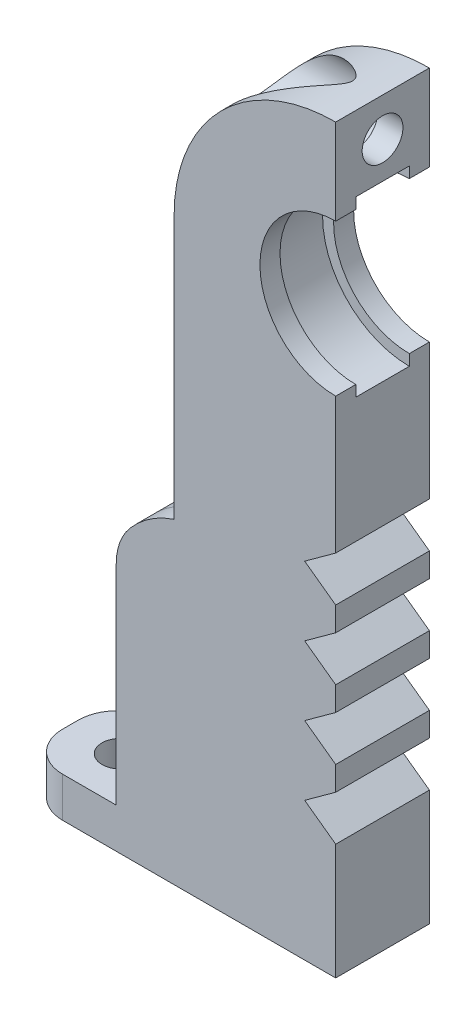
SolidWorks part; units mm, degrees
ref_plane "Front Plane" through (0, 0, 0) normal (0, 0, 1) x (1, 0, 0)
ref_plane "Top Plane" through (0, 0, 0) normal (0, 1, 0) x (1, 0, 0)
ref_plane "Right Plane" through (0, 0, 0) normal (1, 0, 0) x (0, 0, -1)
sketch "Sketch2" plane through (0, 0, 0) normal (0, 0, 1) x (1, 0, 0)
  line L0 (0, 24.5192) -> (0, -19.6154) construction
  line L1 (-22.1654, 0) -> (0, 0) construction
  line L2 (0, -11.11) -> (0, -27.11)
  line L3 (-20.69, 0) -> (-20.69, -33.7064)
  line L4 (0, -74.23) -> (-39.96, -74.23)
  line L5 (-39.96, -74.23) -> (-39.96, -69.11)
  line L6 (-28.1, -42.31) -> (-28.1, -69.11)
  line L7 (-28.1, -69.11) -> (-39.96, -69.11)
  line L9 (0, 11.11) -> (0, 20.69)
  line L10 (11.11, 0) -> (17.0654, 0) construction
  line L11 (0, -74.23) -> (7.8391, -74.23) construction
  line L12 (7.8391, -74.23) -> (7.8391, -63.37) construction
  line L13 (0, -32.87) -> (0, -35.95)
  line L14 (0, -41.71) -> (0, -44.79)
  line L15 (0, -50.55) -> (0, -53.63)
  line L16 (0, -59.39) -> (-3.97, -56.51)
  line L17 (-3.97, -56.51) -> (0, -53.63)
  line L18 (0, -59.39) -> (0, -74.23)
  line L19 (-3.97, -47.67) -> (-16.74, -47.67) construction
  line L20 (-16.74, -47.67) -> (-16.74, -45.66) construction
  line L21 (0, -50.55) -> (-3.97, -47.67)
  line L23 (-3.97, -47.67) -> (0, -44.79)
  line L28 (0, -41.71) -> (-3.97, -38.83)
  line L29 (-3.97, -38.83) -> (0, -35.95)
  line L34 (0, -32.87) -> (-3.97, -29.99)
  line L35 (-3.97, -29.99) -> (0, -27.11)
  arc A0 (0, 11.11) -> (0, -11.11) centre (0, 0) ccw
  arc A1 (0, 20.69) -> (-20.69, 0) centre (0, 0) ccw
  arc A2 (-26.3413, -37.5172) -> (-28.1, -42.31) centre (-20.69, -42.31) ccw
  arc A4 (-20.69, -33.7064) -> (-26.3413, -37.5172) centre (-16.74, -45.66) ccw
  dimension "D1" = 22.22
  dimension "D2" = 9.58
  dimension "D3" = 63.12
  dimension "D6" = 39.96
  dimension "D7" = 5.12
  dimension "D8" = 11.86
  dimension "D9" = 10.86
  dimension "D10" = 8.84
  dimension "D11" = 8.84
  dimension "D12" = 8.84
  dimension "D13" = 5.76
  dimension "D14" = 5.76
  dimension "D15" = 5.76
  dimension "D16" = 5.76
  dimension "D17" = 16
  dimension "D18" = 71.917
  dimension "D19" = 71.917
  dimension "D20" = 71.917
  dimension "D21" = 71.917
  dimension "D22" = 12.77
  dimension "D23" = 2.01
extrude "Boss-Extrude1" add sketch "Sketch2" along normal mid plane 6.86
sketch "Sketch4" plane through (0, 0, 3.43) normal (0, 0, 1) x (1, 0, 0)
  line L0 (-39.96, -69.11) -> (-39.96, -74.23)
  line L1 (-39.96, -74.23) -> (0, -74.23)
  line L2 (0, -74.23) -> (0, -59.39)
  line L3 (0, -59.39) -> (-3.97, -56.51)
  line L4 (0, -59.39) -> (-3.97, -56.51) construction
  line L5 (-3.97, -56.51) -> (0, -53.63)
  line L6 (0, -53.63) -> (0, -50.55)
  line L7 (0, -50.55) -> (-3.97, -47.67)
  line L8 (-3.97, -47.67) -> (0, -44.79)
  line L9 (0, -44.79) -> (0, -41.71)
  line L10 (0, -41.71) -> (-3.97, -38.83)
  line L11 (-3.97, -38.83) -> (0, -35.95)
  line L12 (-3.97, -38.83) -> (0, -35.95) construction
  line L13 (0, -35.95) -> (0, -32.87)
  line L14 (0, -32.87) -> (-3.97, -29.99)
  line L15 (-3.97, -29.99) -> (0, -27.11)
  line L16 (0, 20.69) -> (0, 9.7)
  line L17 (0, -27.11) -> (0, -9.7)
  line L18 (-20.69, -33.7073) -> (-20.69, 0)
  line L19 (-39.96, -69.11) -> (-28.1, -69.11)
  line L20 (-28.1, -42.31) -> (-28.1, -69.11) construction
  line L21 (-28.1, -69.11) -> (-39.96, -69.11) construction
  line L22 (-28.1, -69.11) -> (-28.1, -42.31)
  line L23 (-3.97, -47.67) -> (-16.739, -47.67) construction
  line L24 (-16.739, -47.67) -> (-16.739, -45.6641) construction
  arc A0 (0, 9.7) -> (0, -9.7) centre (0, 0) ccw
  arc A1 (0, 20.69) -> (-20.69, 0) centre (0, 0) ccw
  arc A2 (-26.3389, -37.5144) -> (-28.1, -42.31) centre (-20.69, -42.31) ccw
  arc A3 (-20.69, -33.7073) -> (-26.3389, -37.5144) centre (-16.739, -45.6641) ccw
  dimension "D1" = 10.99
  dimension "D2" = 12.769
  dimension "D3" = 2.0059
extrude "Boss-Extrude3" add sketch "Sketch4" along normal blind 2.57
sketch "Sketch5" plane through (0, 0, -3.43) normal (0, 0, -1) x (-1, 0, 0)
  line L0 (0, 20.69) -> (0, 9.7)
  line L1 (0, -9.7) -> (0, -27.11)
  line L2 (0, -27.11) -> (3.97, -29.99)
  line L3 (3.97, -29.99) -> (0, -32.87)
  line L4 (0, -32.87) -> (0, -35.95)
  line L5 (0, -35.95) -> (3.97, -38.83)
  line L6 (3.97, -38.83) -> (0, -41.71)
  line L7 (0, -41.71) -> (0, -44.79)
  line L8 (0, -44.79) -> (3.97, -47.67)
  line L9 (3.97, -47.67) -> (0, -50.55)
  line L10 (0, -50.55) -> (3.97, -47.67) construction
  line L11 (0, -50.55) -> (0, -53.63)
  line L12 (0, -53.63) -> (3.97, -56.51)
  line L13 (3.97, -56.51) -> (0, -59.39)
  line L14 (0, -59.39) -> (0, -74.23)
  line L15 (0, -74.23) -> (39.96, -74.23)
  line L16 (39.96, -74.23) -> (39.96, -69.11)
  line L17 (39.96, -69.11) -> (28.1, -69.11)
  line L18 (28.1, -69.11) -> (28.1, -42.31)
  line L19 (20.69, -33.7073) -> (20.69, 0)
  arc A0 (20.69, 0) -> (0, 20.69) centre (0, 0) ccw
  arc A1 (0, -9.7) -> (0, 9.7) centre (0, 0) ccw
  arc A2 (28.1, -42.31) -> (26.3389, -37.5144) centre (20.69, -42.31) ccw
  arc A3 (26.3389, -37.5144) -> (20.69, -33.7073) centre (16.739, -45.6641) ccw
  arc A4 (26.3389, -37.5144) -> (20.69, -33.7073) centre (16.739, -45.6641) ccw
  point P1 (0, 0)
  point P47 (0, 0)
  point P50 (0, 0)
  point P53 (0, 0)
  dimension "D1" = 12.5927
sketch "Sketch6" plane through (0, -69.11, 0) normal (0, 1, 0) x (1, 0, 0)
  line L1 (-28.1, -6) -> (-39.96, -6) construction
  line L5 (-28.1, -6) -> (-28.1, 3.43) construction
  circle A0 centre (-33.51, 0) radius 2.41
  dimension "D1" = 4.82
  dimension "D3" = 3
  dimension "D2" = 6
extrude "Cut-Extrude1" cut sketch "Sketch6" against normal through all
sketch "Sketch7" plane through (0, 0, 0) normal (1, 0, 0) x (0, 0, -1)
  line L1 (-6, 20.69) -> (3.43, 20.69) construction
  circle A0 centre (0, 15.78) radius 2.61
  dimension "D1" = 5.22
  dimension "D2" = 2.3
extrude "Cut-Extrude2" cut sketch "Sketch7" against normal through all
sketch "Sketch15" plane through (0, 0, -3.43) normal (0, 0, -1) x (-1, 0, 0)
  line L0 (0, 20.69) -> (0, 9.7)
  line L1 (0, -9.7) -> (0, -27.11)
  line L2 (0, -27.11) -> (3.97, -29.99)
  line L3 (3.97, -29.99) -> (0, -32.87)
  line L4 (0, -32.87) -> (0, -35.95)
  line L5 (0, -35.95) -> (3.97, -38.83)
  line L6 (3.97, -38.83) -> (0, -41.71)
  line L7 (0, -41.71) -> (0, -44.79)
  line L8 (0, -44.79) -> (3.97, -47.67)
  line L9 (3.97, -47.67) -> (0, -50.55)
  line L10 (0, -50.55) -> (0, -53.63)
  line L11 (0, -53.63) -> (3.97, -56.51)
  line L12 (3.97, -56.51) -> (0, -59.39)
  line L13 (0, -59.39) -> (0, -74.23)
  line L14 (0, -74.23) -> (39.96, -74.23)
  line L15 (39.96, -74.23) -> (39.96, -69.11)
  line L16 (39.96, -69.11) -> (28.1, -69.11)
  line L17 (28.1, -69.11) -> (28.1, -42.31)
  line L18 (20.69, 0) -> (20.69, -33.7064)
  arc A0 (20.69, 0) -> (0, 20.69) centre (0, 0) ccw
  arc A1 (0, -9.7) -> (0, 9.7) centre (0, 0) ccw
  arc A2 (28.1, -42.31) -> (26.3389, -37.5144) centre (20.69, -42.31) ccw
  arc A3 (26.3389, -37.5144) -> (20.69, -33.7064) centre (16.7348, -45.6677) ccw
extrude "Boss-Extrude5" add sketch "Sketch15" along normal blind 2.57
fillet "Fillet4" radius 5 2 edges at (-39.96, -71.67, 6) (-39.96, -71.67, -6)
ref_plane "Plane2" through (-3.25, 0, 0) normal (1, 0, 0) x (0, 0, -1)
sketch "Sketch16" plane through (-3.25, 0, 0) normal (1, 0, 0) x (0, 0, -1)
  circle A0 centre (0, 15.78) radius 4.55
  dimension "D1" = 9.1
extrude "Cut-Extrude5" cut sketch "Sketch16" against normal through all
